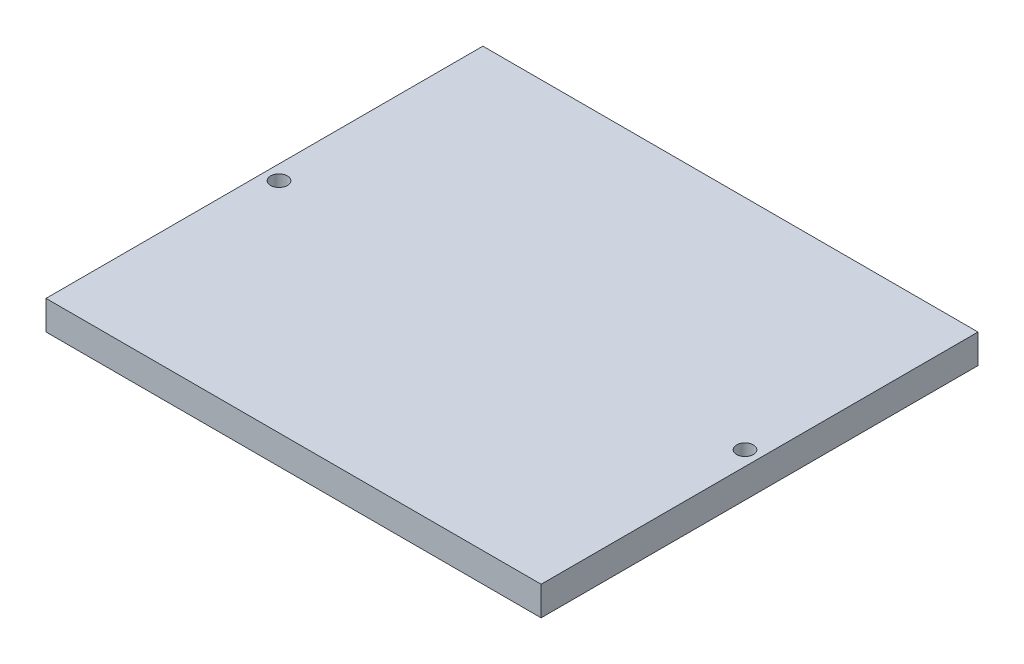
SolidWorks part; units mm, degrees
ref_plane "Front Plane" through (0, 0, 0) normal (0, 0, 1) x (1, 0, 0)
ref_plane "Top Plane" through (0, 0, 0) normal (0, 1, 0) x (1, 0, 0)
ref_plane "Right Plane" through (0, 0, 0) normal (1, 0, 0) x (0, 0, -1)
sketch "Sketch1" plane through (0, 0, 0) normal (0, 1, 0) x (1, 0, 0)
  line L1 (53.975, 47.625) -> (-53.975, 47.625)
  line L2 (53.975, 47.625) -> (53.975, -47.625)
  line L3 (53.975, -47.625) -> (-53.975, -47.625)
  line L4 (-53.975, 47.625) -> (-53.975, -47.625)
  line L5 (53.975, 47.625) -> (-53.975, -47.625) construction
  line L6 (53.975, -47.625) -> (-53.975, 47.625) construction
  point P0 (0, 0)
  dimension "D1" = 107.95
  dimension "D2" = 95.25
extrude "Boss-Extrude1" add sketch "Sketch1" along normal blind 6.35
sketch "Sketch2" plane through (0, 6.35, 0) normal (0, 1, 0) x (1, 0, 0)
  line L0 (-53.975, -47.625) -> (53.975, -47.625) construction
  line L1 (50.8, 47.625) -> (-50.8, 47.625) construction
  line L2 (50.8, 47.625) -> (50.8, -47.625) construction
  line L3 (50.8, -47.625) -> (-50.8, -47.625) construction
  line L4 (-50.8, 47.625) -> (-50.8, -47.625) construction
  line L5 (50.8, 47.625) -> (-50.8, -47.625) construction
  line L6 (50.8, -47.625) -> (-50.8, 47.625) construction
  point P0 (0, 0)
  point P8 (-50.8, 0)
  point P9 (50.8, 0)
  dimension "D1" = 101.6
hole_wizard "#6 Clearance Hole1" positions "Sketch4" profile "Sketch3" hole size "#6" standard "Ansi Inch"
sketch "Sketch4" plane through (0, 6.35, 0) normal (0, 1, 0) x (-1, 0, 0)
  line L0 (50.8, -47.625) -> (50.8, 47.625) construction
  line L1 (-50.8, -47.625) -> (-50.8, 47.625) construction
  point P1 (50.8, 0)
  point P5 (-50.8, 0)
sketch "Sketch3" plane through (-50.8, 6.35, 0) normal (1, 0, 0) x (0, 0, 1)
  line L0 (0, 0) -> (0, 26.4989)
  line L1 (0, 26.4989) -> (1.8288, 25.4)
  line L2 (1.8288, 25.4) -> (1.8288, 0)
  line L5 (1.8288, 0) -> (0, 0)
  line L10 (0, 26.4989) -> (-1.8288, 25.4) construction
  line L11 (0, -6.35) -> (0, 107.95) construction
  dimension "Hole Dia." = 3.6576
  dimension "Hole Depth" = 25.4
  dimension "Drill Angle" = 118
